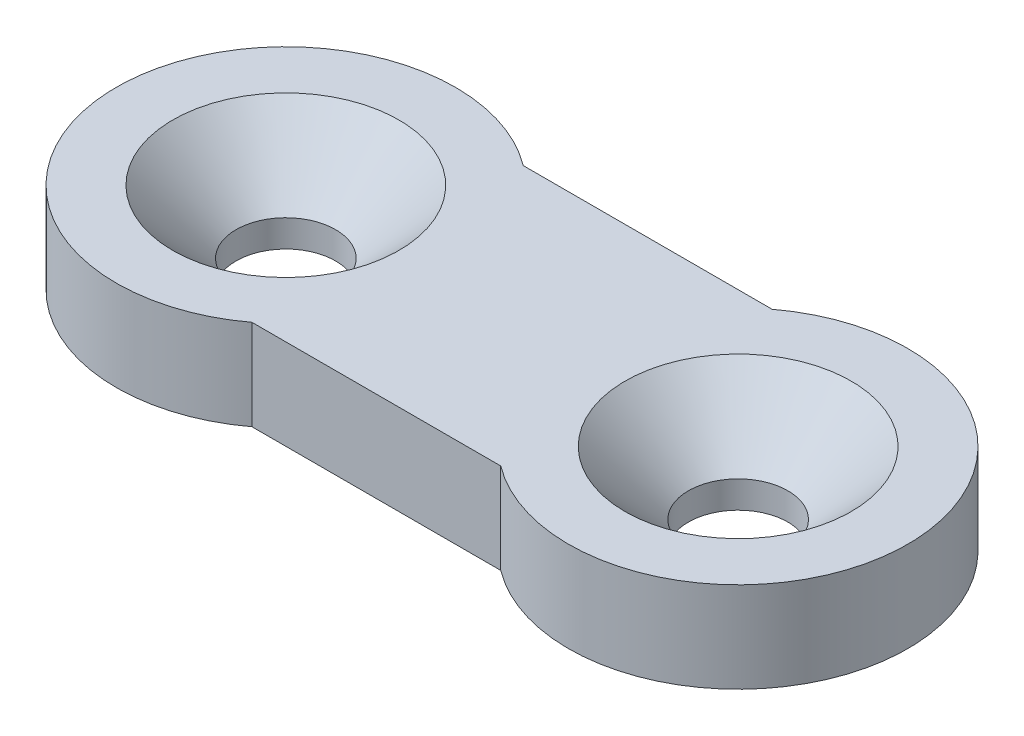
SolidWorks part; units mm, degrees
ref_plane "Front Plane" through (0, 0, 0) normal (0, 0, 1) x (1, 0, 0)
ref_plane "Top Plane" through (0, 0, 0) normal (0, 1, 0) x (1, 0, 0)
ref_plane "Right Plane" through (0, 0, 0) normal (1, 0, 0) x (0, 0, -1)
sketch "Sketch1" plane through (0, 0, 0) normal (0, 1, 0) x (1, 0, 0)
  line L0 (-5, 0) -> (5, 0) construction
  line L1 (-5, 3) -> (5, 3)
  line L2 (-5, -3) -> (5, -3)
  arc A0 (-5, 3) -> (-5, -3) centre (-5, 0) ccw
  arc A1 (5, -3) -> (5, 3) centre (5, 0) ccw
  circle A2 centre (-5, 0) radius 1.1
  circle A5 centre (5, 0) radius 1.1
  point P2 (0, 0)
  dimension "D1" = 2.2
  dimension "D2" = 10
  dimension "D3" = 6
extrude "Boss-Extrude1" add sketch "Sketch1" along normal blind 2
sketch "Sketch3" plane through (0, 2, 0) normal (0, 1, 0) x (1, 0, 0)
  circle A0 centre (-5, 0) radius 3.75
  circle A1 centre (5, 0) radius 3.75
  circle A2 centre (-5, 0) radius 1.1
  circle A3 centre (5, 0) radius 1.1
  circle A4 centre (-5, 0) radius 1.1 construction
  circle A5 centre (5, 0) radius 1.1 construction
  dimension "D1" = 7.5
extrude "Boss-Extrude3" add sketch "Sketch3" against normal up to surface (2 mm away) up to face at (0, 0, 0)
chamfer "Chamfer1" distance 1.4 angle 45 2 edges at (5, 2, 1.1) (-5, 2, 1.1)
